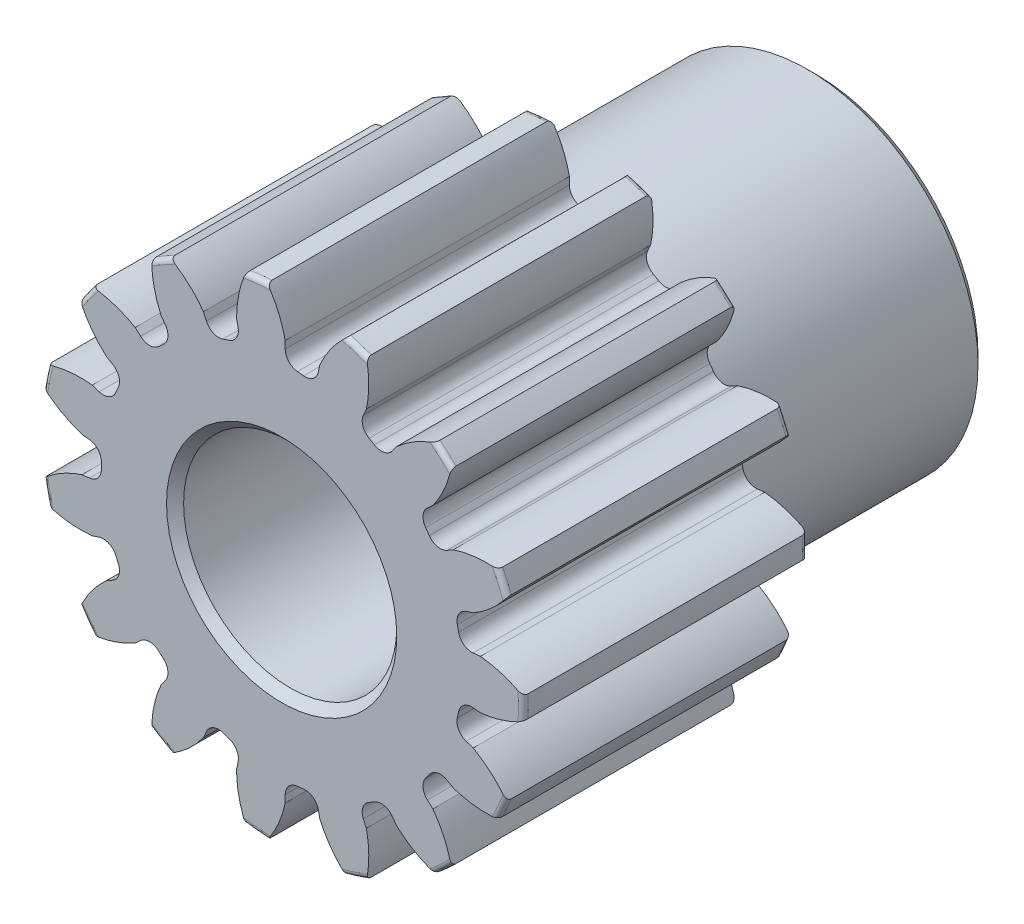
SolidWorks part; units mm, degrees
ref_plane "Front" through (0, 0, 0) normal (0, 0, 1) x (1, 0, 0)
ref_plane "Top" through (0, 0, 0) normal (0, 1, 0) x (1, 0, 0)
ref_plane "Right" through (0, 0, 0) normal (1, 0, 0) x (0, 0, -1)
sketch "Sketch1" plane through (0, 0, 0) normal (0, 0, 1) x (1, 0, 0)
  line L0 (-190.5, 0) -> (190.5, 0) construction
  circle A0 centre (0, 0) radius 10.795
  circle A1 centre (0, 0) radius 9.525 construction
  circle A3 centre (0, 0) radius 8.0556 construction
  dimension "D1" = 1.4694
  dimension "OD" = 21.59
  dimension "Ptich Dia" = 19.05
  dimension "D2" = 2.7394
  dimension "Root Dia" = 16.1112
  dimension "D3" = 1.27
  dimension "Number of Teeth" = 381
extrude "Boss-Extrude1" add sketch "Sketch1" against normal blind 12.7
sketch "Sketch2" plane through (0, 0, 0) normal (1, 0, 0) x (0, 0, -1)
  line L0 (12.7, 0) -> (23.876, 0)
  line L1 (12.7, 0) -> (12.7, 7.62)
  line L2 (12.7, 7.62) -> (23.876, 7.62)
  line L3 (23.876, 7.62) -> (23.876, 0)
  point P5 (23.876, -7.62)
  point P6 (0, -10.795)
  point P7 (12.7, -10.795)
  point P9 (0, 10.795)
  dimension "Face Wd" = 12.7
  dimension "B Hub Dia" = 15.24
  dimension "D O'all Lg." = 23.876
revolve "Revolve1" add sketch "Sketch2" angle 360 mid plane about L0
fillet "Fillet2" radius 0.2159 3 edges at (10.795, 0, -12.7) (10.795, 0, 0) (7.62, 0, -12.7)
sketch "Sketch3" plane through (0, 0, 0) normal (0, 0, 1) x (1, 0, 0)
  line L0 (0, 0) -> (0, 10.795) construction
  line L1 (-3.0613, 8.4108) -> (0, 9.525)
  line L2 (-9.5921, 9.525) -> (9.5921, 9.525) construction
  line L3 (-9.0136, 6.2443) -> (9.0136, 12.8057) construction
  line L4 (-3.0613, 8.4108) -> (0, 0) construction
  line L5 (-7.4633, 4.9409) -> (0, 0) construction
  line L6 (-7.4633, 4.9409) -> (-2.5179, 12.411) construction
  line L7 (-2.1265, 8.6943) -> (0, 0) construction
  line L8 (-2.1265, 8.6943) -> (0.0886, 9.2361) construction
  arc A0 (-3.0613, 8.4108) -> (-7.4633, 4.9409) centre (0, 0) ccw
  circle A1 centre (0, 0) radius 9.525 construction
  circle A2 centre (0, 0) radius 8.9506 construction
  arc A3 (-3.0613, 8.4108) -> (-2.1265, 8.6943) centre (0, 0) cw
  circle A4 centre (0, 0) radius 10.795 construction
  point P6 (0, 9.525)
  dimension "D1" = 3.2577
  dimension "Pressure Angle" = 20
  dimension "D2" = 5.701
  dimension "D3" = 8.9588
  dimension "D4" = 0.9773
  dimension "D5" = 2.2804
sketch "Sketch4" plane through (0, 0, 0) normal (0, 0, 1) x (1, 0, 0)
  line L0 (0, 0) -> (0.9902, 9.4209) construction
  line L1 (0.1581, 8.9492) -> (0.1581, 8.0541)
  line L2 (0, 9.525) -> (1.9804, 9.3169) construction
  line L3 (1.706, 8.7865) -> (1.5199, 7.9109)
  line L4 (0.1581, 8.0541) -> (0, 0) construction
  line L5 (0, 0) -> (0, 10.795) construction
  line L6 (-7.4633, 4.9409) -> (-2.5179, 12.411) construction
  line L7 (-7.4633, 4.9409) -> (-2.5179, 12.411) construction
  arc A0 (1.5199, 7.9109) -> (0.1581, 8.0541) centre (0, 0) ccw
  arc A1 (0, 9.525) -> (1.9804, 9.3169) centre (0, 0) cw construction
  circle A2 centre (0, 0) radius 9.525 construction
  circle A3 centre (0, 0) radius 8.9506 construction
  circle A4 centre (0, 0) radius 8.0556 construction
  arc A5 (5.0432, 11.6163) -> (-2.5179, 12.411) centre (0, 0) ccw
  spline S0 degree 2 poles (-2.5179, 12.411) (-0.3011, 11.1182) (0.1581, 8.9492) knots 0 0 0 1 1 1
  spline S1 degree 2 poles (5.0432, 11.6163) (2.6061, 10.8126) (1.706, 8.7865) knots 0 0 0 1 1 1
  dimension "D1" = 1.9949
extrude "Cut-Extrude1" cut sketch "Sketch4" against normal through all
fillet "Fillet1" radius 0.5985 2 edges at (1.5199, 7.9109, -6.35) (0.1581, 8.0541, -6.35)
pattern_circular "CirPattern1" count 15 over 360 about axis through (0, 0, -12.7) along (0, 0, 1) of "Cut-Extrude1", "Fillet1"
sketch "Sketch5" plane through (0, 0, 0) normal (0, 0, 1) x (1, 0, 0)
  circle A0 centre (0, 0) radius 4.7625
  circle A1 centre (0, 0) radius 4.7625 construction
  dimension "Bore Min" = 9.525
  dimension "Bore Max" = 9.525
extrude "Cut-Extrude2" cut sketch "Sketch5" against normal through all
chamfer "Chamfer1" distance 0.381 angle 45 3 edges at (7.62, 0, -23.876) (4.7625, 0, 0) (4.7625, 0, -23.876)
sketch "Pitch Dia" plane through (0, 0, 0) normal (0, 0, 1) x (1, 0, 0)
  circle A0 centre (0, 0) radius 9.525 construction
  circle A1 centre (0, 0) radius 9.525 construction
equation "\"D1@Boss-Extrude1\" = \"Face Wd@Sketch2\""
equation "\"D2@Sketch3\" = \"D1@Sketch3\"*1.75"
equation "\"D3@Sketch3\" = \"D1@Sketch3\"+\"D2@Sketch3\""
equation "\"D4@Sketch3\" = \"D1@Sketch3\"*.3"
equation "\"D5@Sketch3\" = \"D1@Sketch3\"-\"D4@Sketch3\""
equation "\"D1@Sketch4\" = 1.5708/(\"Number of Teeth@Sketch1\"/\"Ptich Dia@Sketch1\")"
equation "\"D1@Chamfer1\" = \"B Hub Dia@Sketch2\"*.025"
equation "\"D1@CirPattern1\" = \"Number of Teeth@Sketch1\""
equation "\"D1@Fillet1\" = \"D1@Sketch4\"*.3"
equation "\"D1@Fillet2\" = \"OD@Sketch1\"*.01"
equation "\"D1@Sketch1\" = 1.157/(\"Number of Teeth@Sketch1\"/\"Ptich Dia@Sketch1\")"
